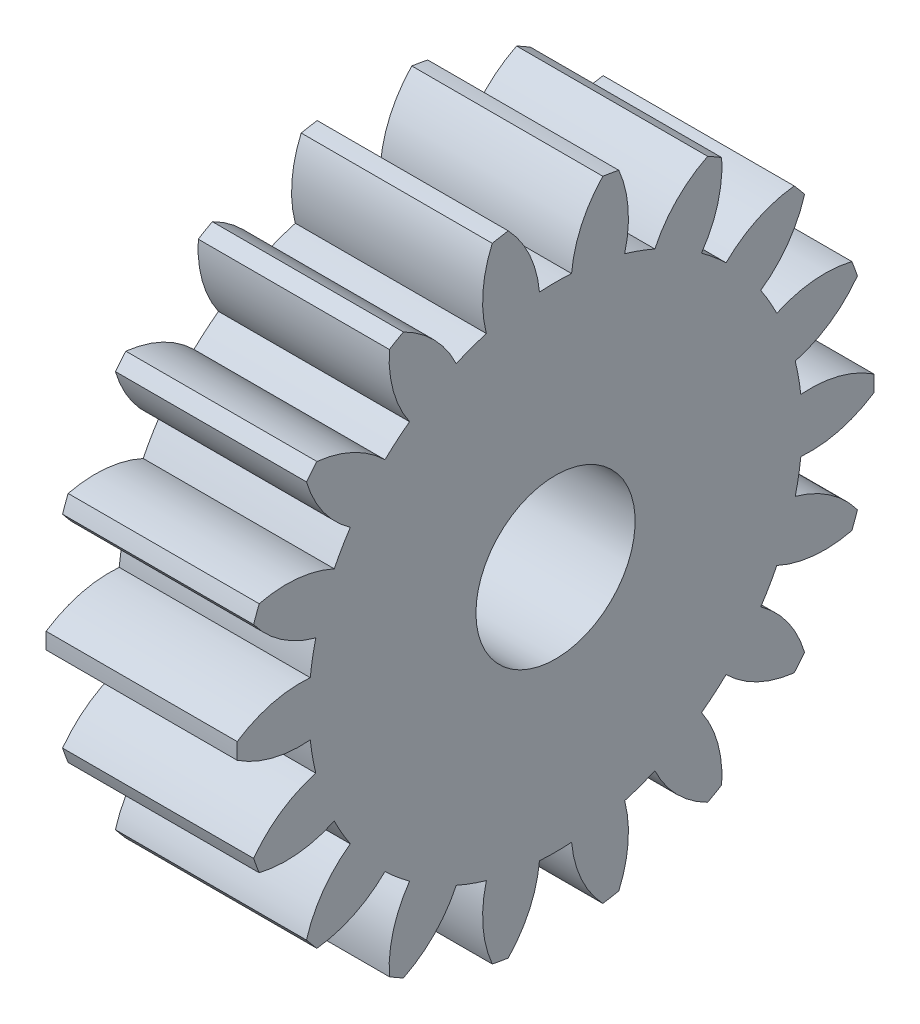
SolidWorks part; units mm, degrees
ref_plane "Plane1" through (0, 0, 0) normal (0, 0, 1) x (1, 0, 0)
ref_plane "Plane2" through (0, 0, 0) normal (0, 1, 0) x (1, 0, 0)
ref_plane "Plane3" through (0, 0, 0) normal (1, 0, 0) x (0, 0, -1)
sketch "HoldingSke" plane through (0, 0, 0) normal (0, 1, 0) x (1, 0, 0)
  line L0 (0, 0) -> (0.4755, -0.1545)
  line L1 (-15, 0) -> (100, 0) construction
  line L2 (0, 0) -> (-2.1039, 2.3779)
  line L3 (0, 0) -> (-11.863, 4.5341)
  line L4 (0, 0) -> (8.2133, 2.6687)
  line L5 (0, 0) -> (-46.8476, -17.4728)
  line L6 (0, 0) -> (-9.9476, -6.7116)
  line L7 (-2.1039, 2.3779) -> (8.6586, 51.2059)
  line L8 (-76.2, 54.61) -> (-74.4, 54.61)
  line L9 (-71.009, 38.7566) -> (-53.1078, 45.2721)
  line L10 (-76.2, 71.12) -> (104.1128, 71.12)
  line L11 (0, 0) -> (-12, 0)
  line L12 (-76.2, 101.6) -> (-76.133, 101.6)
  line L13 (24.9733, 27.94) -> (52.9518, 28.4284)
  line L14 (24.9733, 27.94) -> (24.9743, 27.94)
  line L15 (24.9733, 27.94) -> (100.4006, 29.5858)
  line L16 (-63.627, -2) -> (-12.827, -2)
  circle A0 centre (0, 0) radius 5
  circle A1 centre (0, 0) radius 15.499
  circle A2 centre (0, 0) radius 37.5
  circle A3 centre (0, 0) radius 5
  dimension "MHD" = 30.998
  dimension "Hub_dia" = 75
  dimension "Bore" = 10
  dimension "MBD" = 10
  dimension "Num_teeth" = 18
  dimension "Pitch" = 0.5
  dimension "Overall_len" = 50
  dimension "Show_teeth" = 18
  dimension "Thickness" = 12
  dimension "OAL" = 50.0001
  dimension "T_dim" = 1.8
  dimension "Ap" = 20
  dimension "H" = 19.05
  dimension "Pitch_radius" = 180.3128
  dimension "Width" = 12
  dimension "Backlash" = 0.067
  dimension "Addendum_fac" = 1
  dimension "Dedendum_fac" = 1.25
  dimension "Clearance_fac" = 0.25
  dimension "Dedendum_add" = 0.001
  dimension "Module" = 2
sketch "BasProSke" plane through (0, 0, 0) normal (0, 1, 0) x (1, 0, 0)
  line L0 (-10, 0) -> (60, 0) construction
  line L1 (0, 0) -> (0, 20)
  line L2 (0, 0) -> (12, 0)
  line L3 (12, 0) -> (12, 20)
  line L4 (12, 20) -> (0, 20)
  dimension "Thickness" = 12
  dimension "Diameter" = 40
revolve "Base-Revolve" add sketch "BasProSke" angle 360 about L0
sketch "TooCutSke" plane through (0, 0, 0) normal (1, 0, 0) x (0, 0, -1)
  line L1 (0, 0) -> (0, 107) construction
  line L2 (0, 0) -> (-1.686, 17.9209) construction
  line L3 (0, 0) -> (-6.231, 35.3376) construction
  line L4 (-1.686, 17.9209) -> (-3.1155, 17.6688) construction
  arc A0 (1.0078, 15.4662) -> (-1.0078, 15.4662) centre (0, 0) ccw
  arc A1 (2.9913, 19.8007) -> (-2.9913, 19.8007) centre (0, 0) ccw
  circle A2 centre (0, 0) radius 18 construction
  circle A3 centre (0, 0) radius 16.9145 construction
  arc A4 (-1.0078, 15.4662) -> (-2.9913, 19.8007) centre (-8.1775, 14.8063) ccw
  arc A5 (2.9913, 19.8007) -> (1.0078, 15.4662) centre (8.1775, 14.8063) ccw
  dimension "Root_dia" = 30.998
  dimension "Overcut_dia" = 40.0508
  dimension "Pitch_dia" = 36
  dimension "Base_dia" = 33.8289
  dimension "Flank_rad" = 7.2
  dimension "Half_ang" = 10
  dimension "Half_CT" = 1.4516
extrude "ToothCut" cut sketch "TooCutSke" along normal through all
fillet "Breaks" [suppressed] radius 0.04
fillet "RootFillets" [suppressed] radius 0.501
pattern_circular "TeethCuts" count 18 every 20 about axis through (-10, 0, 0) along (1, 0, 0) of "ToothCut", "RootFillets", "Breaks"
sketch "HubNeaOneSke" plane through (0, 0, 0) normal (-1, 0, 0) x (0, 0, 1)
  circle A0 centre (0, 0) radius 15.499
  dimension "Diameter" = 30.998
extrude "HubNearOne" [suppressed] add sketch "HubNeaOneSke" along normal blind 38.0001
sketch "HubNeaBotSke" plane through (0, 0, 0) normal (-1, 0, 0) x (0, 0, 1)
  circle A0 centre (0, 0) radius 15.499
  dimension "Diameter" = 30.998
extrude "HubNearBoth" [suppressed] add sketch "HubNeaBotSke" along normal blind 19
ref_plane "FarPln" through (12, 0, 0) normal (1, 0, 0) x (0, 0, -1)
sketch "HubFarSke" plane through (12, 0, 0) normal (1, 0, 0) x (0, 0, -1)
  circle A0 centre (0, 0) radius 15.499
  dimension "Diameter" = 30.998
extrude "HubFar" [suppressed] add sketch "HubFarSke" along normal blind 19
sketch "BorSke" plane through (0, 0, 0) normal (1, 0, 0) x (0, 0, -1)
  circle A0 centre (0, 0) radius 5
  dimension "Diameter" = 10
extrude "Bore" cut sketch "BorSke" along normal mid plane 100.0001
sketch "KeySke" plane through (0, 0, 0) normal (1, 0, 0) x (0, 0, -1)
  line L0 (-2, 0) -> (-2, 6.8)
  line L1 (-2, 6.8) -> (2, 6.8)
  line L2 (2, 6.8) -> (2, 0)
  line L3 (0, 0) -> (0, 34) construction
  line L4 (-2, 0) -> (2, 0)
  dimension "Offset" = 6.8
  dimension "Width" = 4
extrude "Keyway" [suppressed] cut sketch "KeySke" along normal mid plane 100.0001
pattern_circular "Keyway2" [suppressed] count 2 every 90 about axis through (-10, 0, 0) along (1, 0, 0)
equation "' \"Module@HoldingSke\" = 6.35"
equation "' \"Num_teeth@HoldingSke\" = 12"
equation "' \"Ap@HoldingSke\" =  20"
equation "' \"Ap@HoldingSke\" = 20"
equation "' \"Width@HoldingSke\" = 0.5 * 25.4"
equation "' \"Hub_dia@HoldingSke\"= 1 * 25.4"
equation "' \"Hub_dia@HoldingSke\" = 1 * 25.4"
equation "' \"Overall_len@HoldingSke\" = 1.0 * 25.4"
equation "' \"Bore@HoldingSke\" = 0.75 * 25.4"
equation "' \"T_dim@HoldingSke\" = 0.1 * 25.4"
equation "' \"Width@KeySke\" = 0.25 * 25.4"
equation "' \"Show_teeth@HoldingSke\" = 13"
equation "' \"Backlash@HoldingSke\" = 0.009 * 25.4"
equation "' \"Addendum_fac@HoldingSke\" = 1.0"
equation "' \"Dedendum_fac@HoldingSke\" = 1.25"
equation "' \"Dedendum_add@HoldingSke\" = 0.00005 * 25.4"
equation "' \"Clearance_fac@HoldingSke\" = 0.25"
equation "\"Pitch@HoldingSke\" = 1 / \"Module@HoldingSke\""
equation "\"Overcut_dia@TooCutSke\" = (\"Num_teeth@HoldingSke\" + 2 * \"Addendum_fac@HoldingSke\") / \"Pitch@HoldingSke\" + 0.002 * 25.4"
equation "\"Pitch_dia@TooCutSke\" = \"Num_teeth@HoldingSke\" / \"Pitch@HoldingSke\""
equation "\"Base_dia@TooCutSke\" = \"Num_teeth@HoldingSke\" / \"Pitch@HoldingSke\" * cos((\"Ap@HoldingSke\"  * 3.14159265 / 180))"
equation "\"Root_dia@TooCutSke\" = (\"Num_teeth@HoldingSke\" + 2) / \"Pitch@HoldingSke\" - 2 * (\"Addendum_fac@HoldingSke\" + \"Dedendum_fac@HoldingSke\") / \"Pitch@HoldingSke\" - \"Dedendum_add@HoldingSke\" * 2"
equation "\"Half_ang@TooCutSke\" = 180 / \"Num_teeth@HoldingSke\""
equation "\"Half_CT@TooCutSke\" = \"Num_teeth@HoldingSke\" / \"Pitch@HoldingSke\" * sin((3.14159265 / 2 / \"Num_teeth@HoldingSke\")) / 2 - 7 * \"Backlash@HoldingSke\" / 4"
equation "\"Flank_rad@TooCutSke\" = \"Num_teeth@HoldingSke\" / \"Pitch@HoldingSke\" / 5"
equation "\"Radius@RootFillets\" = \"Clearance_fac@HoldingSke\" / \"Pitch@HoldingSke\" + \"Dedendum_add@HoldingSke\""
equation "\"Break_rad@Breaks\" = 0.02 / \"Pitch@HoldingSke\""
equation "\"Thickness@HoldingSke\" = \"Width@HoldingSke\""
equation "\"OAL@HoldingSke\" = \"Thickness@HoldingSke\""
equation "\"MHD@HoldingSke\" = (\"Num_teeth@HoldingSke\" + 2) / \"Pitch@HoldingSke\" - 2 * (\"Addendum_fac@HoldingSke\" + \"Dedendum_fac@HoldingSke\")  / \"Pitch@HoldingSke\" - \"Dedendum_add@HoldingSke\" * 2"
equation "\"MBD@HoldingSke\" = (\"Num_teeth@HoldingSke\" + 2) / \"Pitch@HoldingSke\" - 2 * (\"Addendum_fac@HoldingSke\" + \"Dedendum_fac@HoldingSke\")  / \"Pitch@HoldingSke\" - \"Dedendum_add@HoldingSke\" * 2 - 0.002 * 25.4"
equation "\"MHD@HoldingSke\" = ((sgn( \"MHD@HoldingSke\" - \"Hub_dia@HoldingSke\" )-1)*( \"MHD@HoldingSke\" - \"Hub_dia@HoldingSke\" ))/-2+ \"Hub_dia@HoldingSke\""
equation "\"MBD@HoldingSke\" = ((sgn( \"MBD@HoldingSke\" - \"Bore@HoldingSke\" )-1)*( \"MBD@HoldingSke\" - \"Bore@HoldingSke\" ))/-2+ \"Bore@HoldingSke\""
equation "\"OAL@HoldingSke\" = ((sgn( \"OAL@HoldingSke\" - \"Overall_len@HoldingSke\" )+1)*( \"OAL@HoldingSke\" - \"Overall_len@HoldingSke\" ))/2 + \"Overall_len@HoldingSke\" + 0.000002 * 25.4"
equation "\"Num_teeth@TeethCuts\" = int( \"Show_teeth@HoldingSke\" ) + 1"
equation "\"Num_teeth@TeethCuts\" = ((sgn( \"Num_teeth@TeethCuts\" - \"Num_teeth@HoldingSke\" )-1)*( \"Num_teeth@TeethCuts\" - \"Num_teeth@HoldingSke\" ))/-2+ \"Num_teeth@HoldingSke\""
equation "\"Num_teeth@TeethCuts\" = ((sgn( \"Num_teeth@TeethCuts\" - 2.0)+1)*( \"Num_teeth@TeethCuts\" - 2.0))/2 +2.0"
equation "\"Angle@TeethCuts\" = 360.0 / \"Num_teeth@HoldingSke\""
equation "\"Diameter@BasProSke\" = (\"Num_teeth@HoldingSke\" + 2 * \"Addendum_fac@HoldingSke\") / \"Pitch@HoldingSke\""
equation "\"Thickness@BasProSke\"  = \"Thickness@HoldingSke\""
equation "' \"Fillet_rad@BasProSke\" =  \"Thickness@HoldingSke\" * 0.05"
equation "' \"Fillet_rad@BasProSke\" = \"Thickness@HoldingSke\" * 0.05"
equation "\"MHD@HoldingSke\" = ((sgn( \"MHD@HoldingSke\" - \"Root_dia@TooCutSke\" )-1)*( \"MHD@HoldingSke\" - \"Root_dia@TooCutSke\" ))/-2+ \"Root_dia@TooCutSke\""
equation "\"Diameter@HubNeaOneSke\" = \"MHD@HoldingSke\""
equation "\"Length@HubNearOne\" = \"OAL@HoldingSke\" - \"Thickness@BasProSke\""
equation "\"Diameter@HubNeaBotSke\" = \"MHD@HoldingSke\""
equation "\"Length@HubNearBoth\" = ( \"OAL@HoldingSke\" - \"Thickness@BasProSke\" ) / 2.0"
equation "\"Thickness@FarPln\" = \"Thickness@BasProSke\""
equation "\"Diameter@HubFarSke\" = \"MHD@HoldingSke\""
equation "\"Length@HubFar\" = ( \"OAL@HoldingSke\" - \"Thickness@BasProSke\" ) / 2.0"
equation "\"Diameter@BorSke\" = \"MBD@HoldingSke\""
equation "\"D1@Bore\" = \"OAL@HoldingSke\" * 2.0"
equation "\"D1@Keyway\" = \"OAL@HoldingSke\" * 2.0"
equation "\"Offset@KeySke\" = \"T_dim@HoldingSke\" + \"MBD@HoldingSke\" / 2.0"
